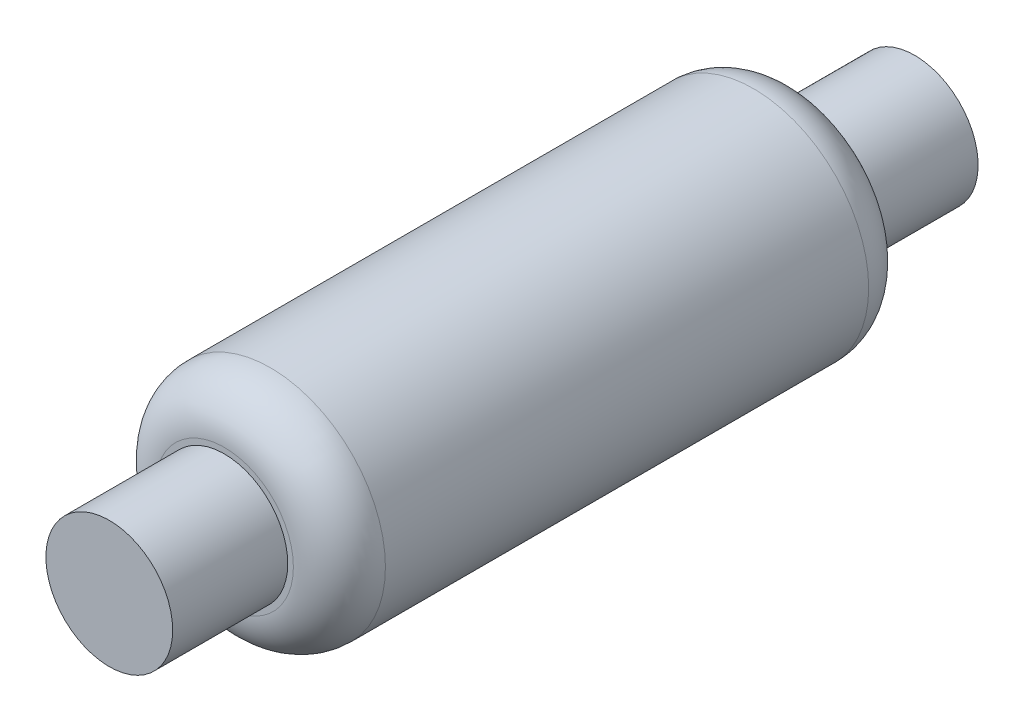
SolidWorks part; units mm, degrees
ref_plane "Plan de face" through (0, 0, 0) normal (0, 0, 1) x (1, 0, 0)
ref_plane "Plan de dessus" through (0, 0, 0) normal (0, 1, 0) x (1, 0, 0)
ref_plane "Plan de droite" through (0, 0, 0) normal (1, 0, 0) x (0, 0, -1)
sketch "Esquisse1" plane through (0, 0, 0) normal (0, 0, 1) x (1, 0, 0)
  circle A0 centre (0, 0) radius 5
  dimension "D1" = 10
extrude "Boss.-Extru.1" add sketch "Esquisse1" along normal blind 25
sketch "Esquisse2" plane through (0, 0, 25) normal (0, 0, 1) x (1, 0, 0)
  circle A0 centre (0, 0) radius 2.755
  dimension "D1" = 5.51
extrude "Boss.-Extru.2" add sketch "Esquisse2" along normal blind 5
sketch "Esquisse3" plane through (0, 0, 0) normal (0, 0, -1) x (-1, 0, 0)
  circle A0 centre (0, 0) radius 2.755
  dimension "D1" = 5.51
extrude "Boss.-Extru.3" add sketch "Esquisse3" along normal blind 5
fillet "Congé2" radius 2 1 edges at (5, 0, 0)
fillet "Congé3" radius 2 1 edges at (5, 0, 25)
